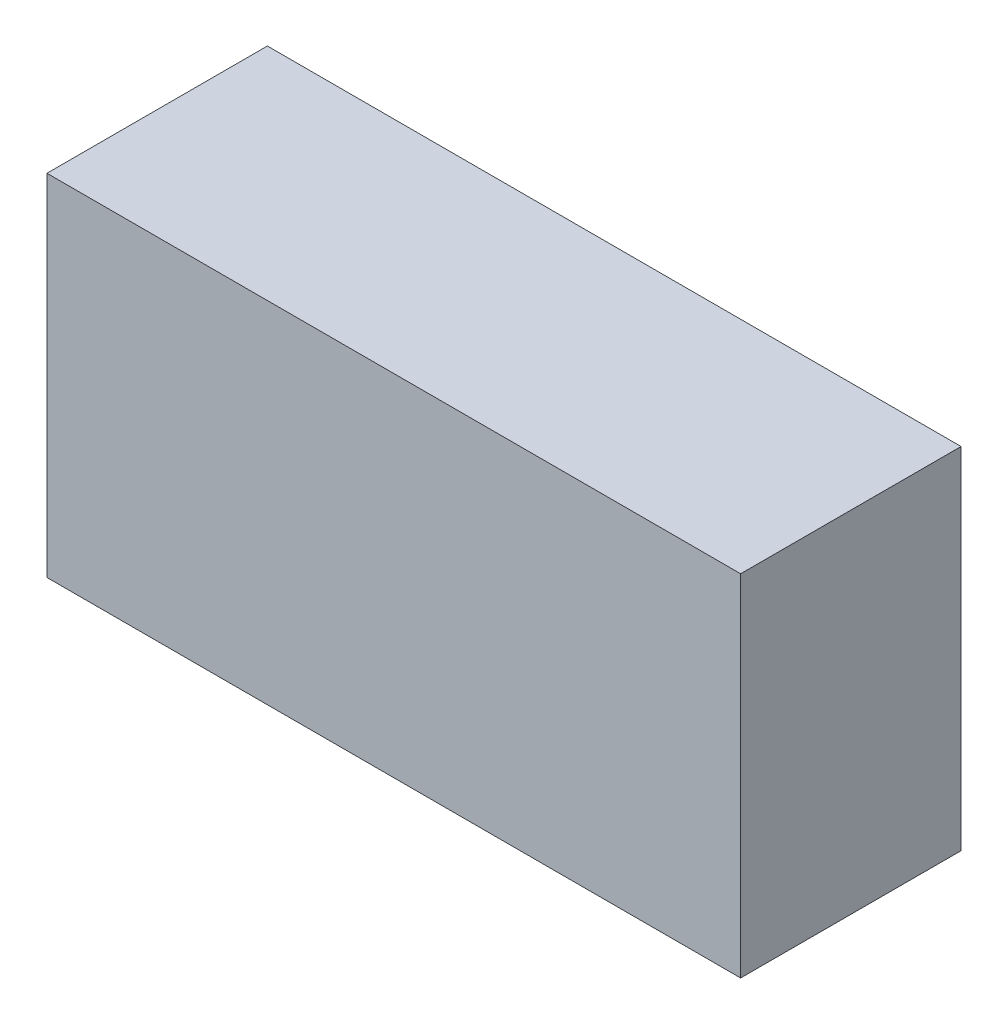
SolidWorks part; units mm, degrees
ref_plane "Front Plane" through (0, 0, 0) normal (0, 0, 1) x (1, 0, 0)
ref_plane "Top Plane" through (0, 0, 0) normal (0, 1, 0) x (1, 0, 0)
ref_plane "Right Plane" through (0, 0, 0) normal (1, 0, 0) x (0, 0, -1)
other "Bounding Box"
ref_plane "Default Plane" through (-8.9266, -12.7485, 0) normal (-0.1736, 0.9848, 0) x (0.9848, 0.1736, 0)
sketch "Sketch1" plane through (0, 0, 0) normal (0, 1, 0) x (1, 0, 0)
  line L1 (-26.75, -8.5) -> (26.75, -8.5)
  line L2 (-26.75, -8.5) -> (-26.75, 8.5)
  line L3 (-26.75, 8.5) -> (26.75, 8.5)
  line L4 (26.75, -8.5) -> (26.75, 8.5)
  line L5 (-26.75, -8.5) -> (26.75, 8.5) construction
  line L6 (-26.75, 8.5) -> (26.75, -8.5) construction
  point P0 (0, 0)
  dimension "D1" = 17
  dimension "D2" = 53.5
extrude "Boss-Extrude1" add sketch "Sketch1" along normal blind 27
